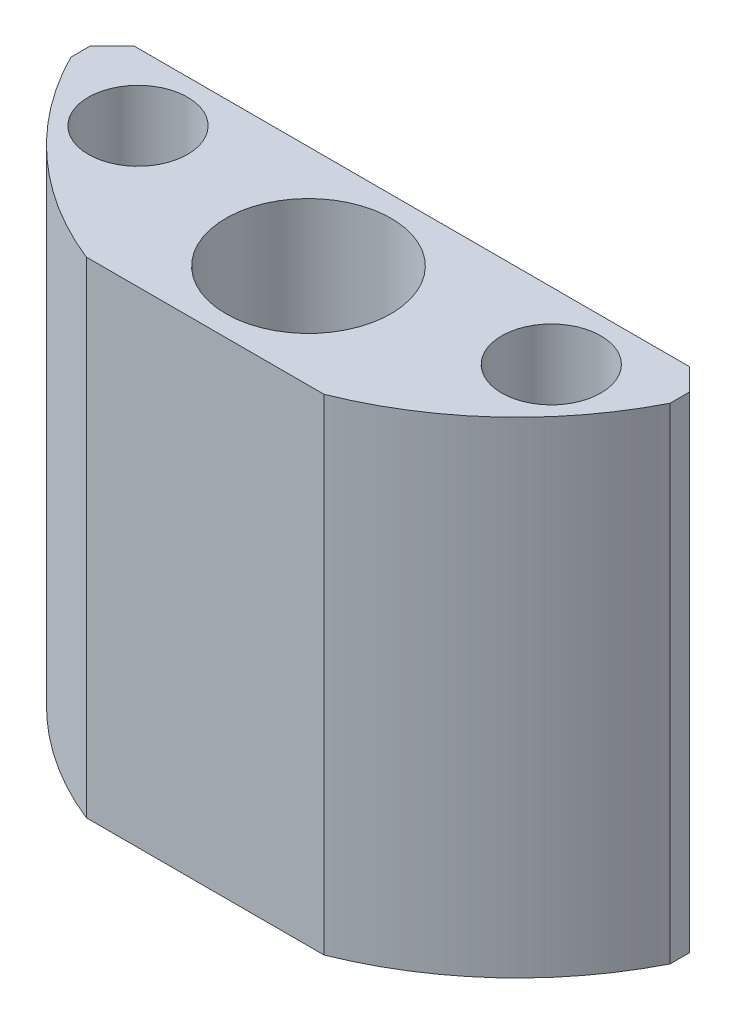
SolidWorks part; units mm, degrees
material "Copper"
ref_plane "Front Plane" through (0, 0, 0) normal (0, 0, 1) x (1, 0, 0)
ref_plane "Top Plane" through (0, 0, 0) normal (0, 1, 0) x (1, 0, 0)
ref_plane "Right Plane" through (0, 0, 0) normal (1, 0, 0) x (0, 0, -1)
sketch "Sketch1" plane through (0, 0, 0) normal (0, 1, 0) x (1, 0, 0)
  line L0 (-26.8787, 0) -> (26.8787, 0)
  line L1 (11.5, -20) -> (-11.5, -20)
  line L2 (-26.8787, 0) -> (-29, -2.1213)
  line L3 (-29, -4) -> (-29, 2.5234) construction
  line L4 (-29, -2.1213) -> (-29, -4)
  line L5 (0, 0) -> (0, -20) construction
  line L6 (29, -2.1213) -> (29, -4)
  line L7 (26.8787, 0) -> (29, -2.1213)
  arc A0 (-29, -4) -> (-11.5, -20) centre (0.8918, 11.1238) ccw
  arc A4 (29, -4) -> (11.5, -20) centre (-0.8918, 11.1238) cw
  dimension "D1" = 29
  dimension "D2" = 33.5
  dimension "D3" = 4
  dimension "D4" = 45
  dimension "D5" = 20
  dimension "D6" = 11.5
  dimension "D7" = 11.1238
  dimension "D8" = 3
extrude "Boss-Extrude1" add sketch "Sketch1" against normal blind 47
sketch "Sketch2" plane through (0, 0, 0) normal (0, 1, 0) x (1, 0, 0)
  line L0 (26.8787, 0) -> (-26.8787, 0) construction
  circle A0 centre (-20, -6.5) radius 4
  circle A1 centre (0, -10) radius 8
  circle A2 centre (20, -6.5) radius 4
  dimension "D1" = 8
  dimension "D5" = 16
  dimension "D6" = 8
  dimension "D2" = 20
  dimension "D3" = 6.5
  dimension "D4" = 10
  dimension "D7" = 20
  dimension "D8" = 6.5
extrude "Cut-Extrude1" cut sketch "Sketch2" against normal through all
sketch "Sketch3" plane through (0, 0, 0) normal (0, 1, 0) x (1, 0, 0)
  circle A0 centre (-20, -6.5) radius 4.8
  circle A1 centre (20, -6.5) radius 4.8
  dimension "D1" = 9.6
  dimension "D2" = 9.6
extrude "Cut-Extrude2" cut sketch "Sketch3" against normal blind 37.5
